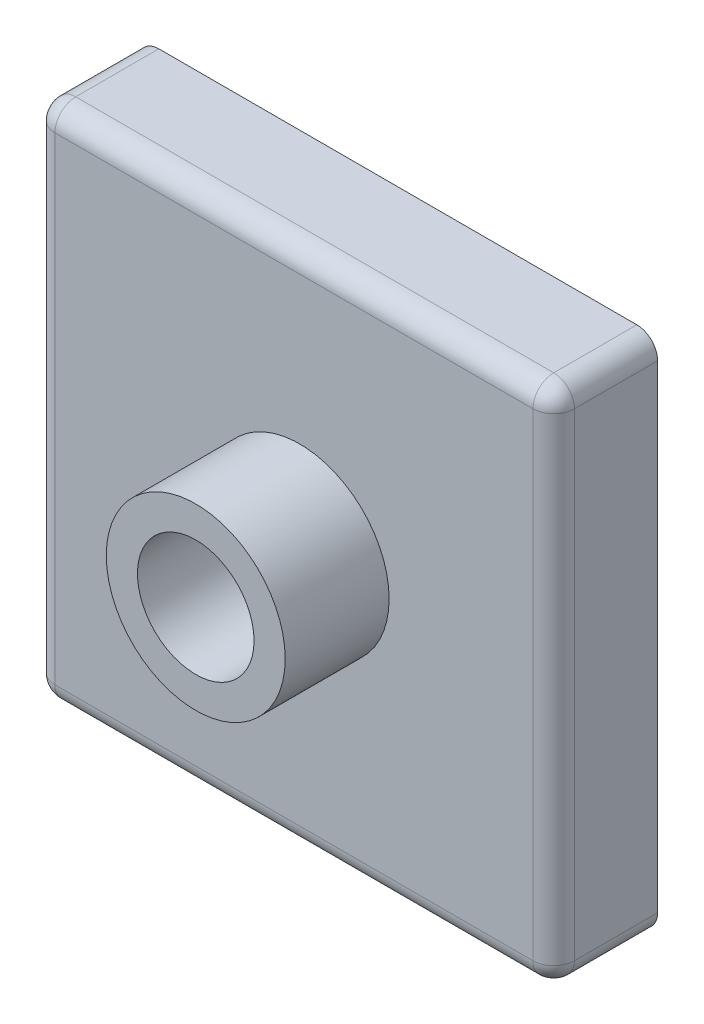
SolidWorks part; units mm, degrees
ref_plane "Front Plane" through (0, 0, 0) normal (0, 0, 1) x (1, 0, 0)
ref_plane "Top Plane" through (0, 0, 0) normal (0, 1, 0) x (1, 0, 0)
ref_plane "Right Plane" through (0, 0, 0) normal (1, 0, 0) x (0, 0, -1)
sketch "Sketch1" plane through (0, 0, 0) normal (0, 0, 1) x (1, 0, 0)
  line L1 (0, 0) -> (1270, 0)
  line L2 (0, 0) -> (0, -1270)
  line L3 (0, -1270) -> (1270, -1270)
  line L4 (1270, 0) -> (1270, -1270)
  dimension "D1" = 1270
  dimension "D2" = 1270
extrude "Boss-Extrude1" add sketch "Sketch1" along normal blind 254
sketch "Sketch2" plane through (15.7561, -33.2628, 254) normal (0, 0, 1) x (1, 0, 0)
  circle A0 centre (633.2493, -595.6098) radius 218.6941
extrude "Boss-Extrude2" add sketch "Sketch2" along normal blind 254
fillet "Fillet2" radius 50.8 1 edges at (1270, -635, 254)
fillet "Fillet3" radius 50.8 3 edges at (1270, 0, 101.6) (1255.121, 0, 239.121) (609.6, 0, 254)
fillet "Fillet4" radius 50.8 3 edges at (1270, -1270, 101.6) (1255.121, -1270, 239.121) (609.6, -1270, 254)
fillet "Fillet5" radius 50.8 5 edges at (0, 0, 101.6) (0, -14.879, 239.121) (0, -1270, 101.6) (0, -1255.121, 239.121) (0, -635, 254)
sketch "Sketch4" plane through (0, 0, 508) normal (0, 0, 1) x (1, 0, 0)
  circle A6 centre (649.0054, -628.8726) radius 142.4941
  circle A7 centre (649.0054, -628.8726) radius 142.4941
  dimension "D1" = 76.2
extrude "Cut-Extrude13" cut sketch "Sketch4" against normal through all
shell "Shell4" thickness 76.2
